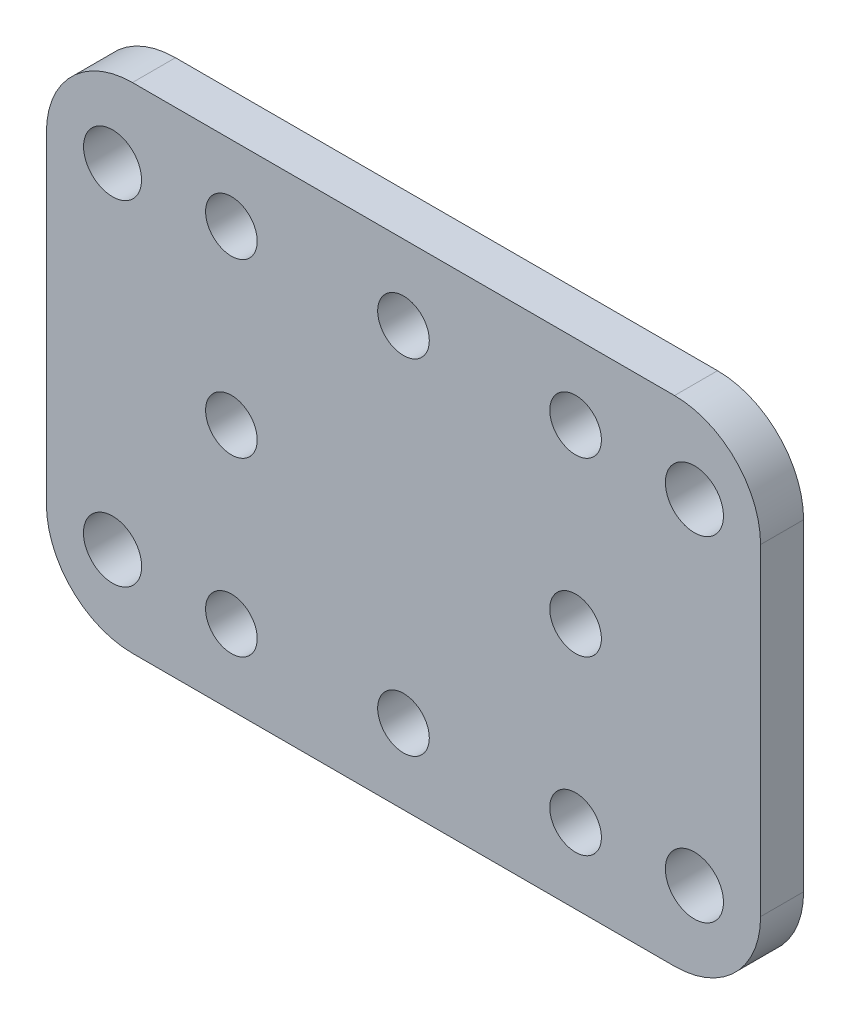
SolidWorks part; units mm, degrees
ref_plane "Alzado" through (0, 0, 0) normal (0, 0, 1) x (1, 0, 0)
ref_plane "Planta" through (0, 0, 0) normal (0, 1, 0) x (1, 0, 0)
ref_plane "Vista lateral" through (0, 0, 0) normal (1, 0, 0) x (0, 0, -1)
sketch "Croquis1" plane through (0, 0, 0) normal (0, 0, 1) x (1, 0, 0)
  line L0 (-0.0106, 23.1539) -> (33.1904, 23.1539)
  line L5 (-0.0106, 23.1539) -> (-0.0106, 0.1756)
  line L6 (-0.0106, 0.1756) -> (33.1904, 0.1756)
  line L7 (33.1904, 23.1539) -> (33.1904, 0.1756)
  circle A0 centre (3.0649, 19.4414) radius 1.3479
  circle A1 centre (30.1148, 19.4414) radius 1.35
  circle A2 centre (30.1148, 3.8881) radius 1.35
  circle A3 centre (3.0649, 3.8881) radius 1.3526
extrude "Saliente-Extruir1" add sketch "Croquis1" along normal blind 2 contours L0 L7 L6 L5
sketch "Croquis3" plane through (0, 0, 0) normal (0, 0, -1) x (-1, 0, 0)
  circle A0 centre (-30.1148, 19.4414) radius 1.35
  circle A1 centre (-3.0649, 19.4414) radius 1.3479
  circle A2 centre (-3.0649, 3.8881) radius 1.3526
  circle A3 centre (-30.1148, 3.8881) radius 1.35
extrude "Cortar-Extruir2" cut sketch "Croquis3" against normal through all
fillet "Redondeo2" radius 4 2 edges at (33.1904, 0.1756, 1) (33.1904, 23.1539, 1)
fillet "Redondeo3" radius 4 2 edges at (-0.0106, 0.1756, 1) (-0.0106, 23.1539, 1)
sketch "Croquis4" plane through (0, 0, 2) normal (0, 0, 1) x (1, 0, 0)
  line L0 (16.5899, 3.6647) -> (16.5899, 0.1756) construction
  line L1 (8.5899, 19.6647) -> (24.5899, 19.6647)
  line L2 (8.5899, 19.6647) -> (8.5899, 3.6647)
  line L3 (8.5899, 3.6647) -> (24.5899, 3.6647)
  line L4 (24.5899, 19.6647) -> (24.5899, 3.6647)
  line L5 (3.9894, 0.1756) -> (29.1904, 0.1756) construction
  line L6 (16.5899, 23.1539) -> (16.5899, 19.6647) construction
  line L7 (24.5899, 11.6647) -> (33.1904, 11.6647) construction
  line L8 (33.1904, 19.1539) -> (33.1904, 4.1756) construction
  line L9 (3.9894, 23.1539) -> (29.1904, 23.1539) construction
  line L10 (8.5899, 11.6647) -> (-0.0106, 11.6647) construction
  line L11 (-0.0106, 19.1539) -> (-0.0106, 4.1756) construction
  circle A0 centre (8.5899, 19.6647) radius 1.2
  circle A1 centre (16.5899, 19.6647) radius 1.2
  circle A2 centre (24.5899, 19.6647) radius 1.2
  circle A3 centre (8.5899, 11.6647) radius 1.2
  circle A4 centre (24.5899, 11.6647) radius 1.2
  circle A5 centre (8.5899, 3.6647) radius 1.2
  circle A6 centre (16.5899, 3.6647) radius 1.2
  circle A7 centre (24.5899, 3.6647) radius 1.2
  dimension "D1" = 16
extrude "Cortar-Extruir3" cut sketch "Croquis4" against normal through all contours L1 A0 L2 | L2 A0 L1 | L2 A3 | L2 A3 | L2 A5 L3 | L3 A5 L2 | L3 A6 | L3 A6 | L3 A7 L4 | L4 A7 L3 | L4 A4 | L4 A4 | L4 A2 L1 | L1 A2 L4 | L1 A1 | L1 A1
